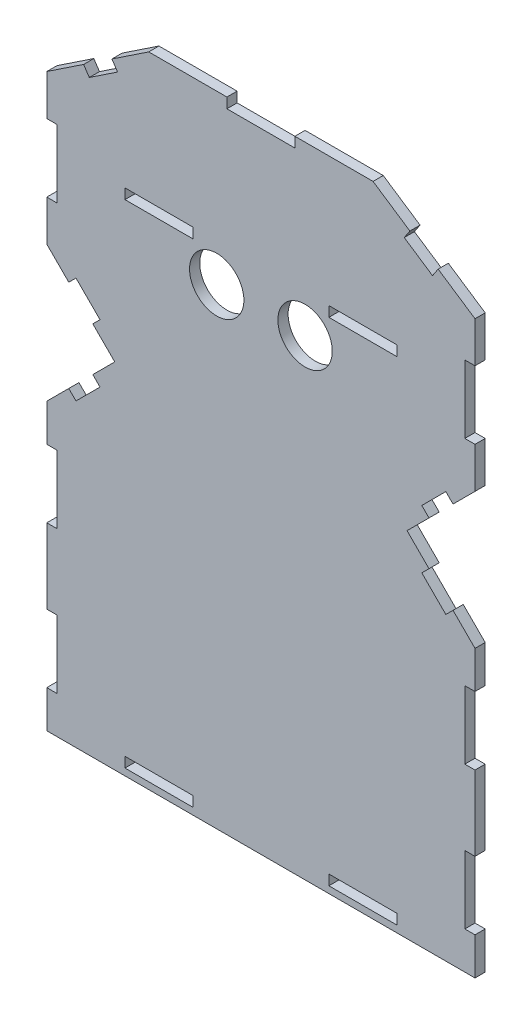
SolidWorks part; units mm, degrees
ref_plane "Front Plane" through (0, 0, 0) normal (0, 0, 1) x (1, 0, 0)
ref_plane "Top Plane" through (0, 0, 0) normal (0, 1, 0) x (1, 0, 0)
ref_plane "Right Plane" through (0, 0, 0) normal (1, 0, 0) x (0, 0, -1)
sketch "Sketch1" plane through (0, 0, 0) normal (0, 0, 1) x (1, 0, 0)
  line L0 (62.2747, 0) -> (62.2747, -11)
  line L1 (-33.7253, 104) -> (-10.7253, 104)
  line L2 (-63.7253, 84) -> (-63.7253, 72)
  line L3 (-63.7253, -84) -> (62.2747, -84)
  line L4 (62.2747, 84) -> (62.2747, 72)
  line L5 (-0.7253, -84) -> (-0.7253, -49.3815) construction
  line L6 (-63.7253, -84) -> (-63.7253, -80.5) construction
  line L7 (-63.7253, -80.5) -> (-60.7253, -80.5) construction
  line L8 (-63.7253, 84) -> (-52.8856, 91.2265)
  line L10 (-63.7253, 84) -> (-63.7253, 72) construction
  line L11 (-60.7253, -80.5) -> (-60.7253, -84) construction
  line L12 (-63.7253, 0) -> (-57.2608, 6.4645)
  line L13 (-43.7253, 20) -> (-50.1898, 26.4645)
  line L14 (62.2747, 0) -> (55.8102, 6.4645)
  line L15 (42.2747, 20) -> (48.7392, 26.4645)
  line L16 (-63.7253, 0) -> (-63.7253, -11)
  line L17 (62.2747, -80.5) -> (59.2747, -80.5) construction
  line L18 (-60.7253, -80.5) -> (59.2747, -80.5) construction
  line L19 (-0.7253, -80.5) -> (-60.7253, -80.5) construction
  line L20 (19.2747, -82) -> (19.2747, -79)
  line L21 (-40.7253, -82) -> (-20.7253, -82)
  line L22 (-40.7253, -82) -> (-40.7253, -79)
  line L23 (-40.7253, -79) -> (-20.7253, -79)
  line L24 (-20.7253, -82) -> (-20.7253, -79)
  line L25 (-40.7253, -82) -> (-20.7253, -79) construction
  line L26 (-40.7253, -79) -> (-20.7253, -82) construction
  line L27 (39.2747, -82) -> (19.2747, -82)
  line L28 (39.2747, -82) -> (39.2747, -79)
  line L29 (39.2747, -79) -> (19.2747, -79)
  line L30 (-63.7253, -84) -> (-62.221, -84) construction
  line L31 (-63.7253, -42) -> (-62.2253, -42) construction
  line L32 (-62.2253, -42) -> (-62.2253, 0) construction
  line L33 (-62.2253, 0) -> (-63.7253, 0) construction
  line L34 (-63.7253, -31) -> (-60.7253, -31)
  line L36 (-63.7253, -11) -> (-60.7253, -11)
  line L37 (-60.7253, -31) -> (-60.7253, -11)
  line L38 (-63.7253, -31) -> (-60.7253, -11) construction
  line L39 (-63.7253, -11) -> (-60.7253, -31) construction
  line L40 (-63.7253, -53) -> (-60.7253, -53)
  line L41 (-60.7253, -53) -> (-60.7253, -73)
  line L42 (-63.7253, -73) -> (-60.7253, -73)
  line L43 (-62.2253, -84) -> (-63.7253, -84) construction
  line L44 (62.2747, -53) -> (59.2747, -53)
  line L45 (59.2747, -53) -> (59.2747, -73)
  line L46 (62.2747, -73) -> (59.2747, -73)
  line L47 (62.2747, -31) -> (59.2747, -31)
  line L48 (62.2747, -11) -> (59.2747, -11)
  line L49 (59.2747, -31) -> (59.2747, -11)
  line L50 (-63.7253, -73) -> (-63.7253, -84)
  line L51 (62.2747, -73) -> (62.2747, -84)
  line L52 (62.2747, -31) -> (62.2747, -53)
  line L53 (-63.7253, -31) -> (-63.7253, -53)
  line L54 (-63.7253, 40) -> (-62.2253, 40) construction
  line L55 (-62.2253, 40) -> (-62.2253, 84) construction
  line L56 (-62.2253, 84) -> (-63.7253, 84) construction
  line L57 (-63.7253, 52) -> (-63.7253, 40)
  line L58 (-63.7253, 52) -> (-60.7253, 52)
  line L60 (-63.7253, 72) -> (-60.7253, 72)
  line L61 (-60.7253, 52) -> (-60.7253, 72)
  line L62 (-63.7253, 52) -> (-60.7253, 72) construction
  line L63 (-63.7253, 72) -> (-60.7253, 52) construction
  line L64 (-63.7253, 52) -> (-63.7253, 40) construction
  line L65 (62.2747, 52) -> (59.2747, 52)
  line L66 (59.2747, 52) -> (59.2747, 72)
  line L67 (62.2747, 72) -> (59.2747, 72)
  line L68 (62.2747, 52) -> (62.2747, 40)
  line L69 (-43.7253, 20) -> (-42.6646, 18.9393) construction
  line L70 (-63.7253, 0) -> (-62.6646, -1.0607) construction
  line L71 (-62.6646, -1.0607) -> (-42.6646, 18.9393) construction
  line L72 (-55.1395, 4.3431) -> (-57.2608, 6.4645)
  line L73 (-55.1395, 4.3431) -> (-48.0685, 11.4142)
  line L75 (-48.0685, 11.4142) -> (-50.1898, 13.5355)
  line L76 (-50.1898, 13.5355) -> (-43.7253, 20)
  line L77 (53.6889, 4.3431) -> (55.8102, 6.4645)
  line L78 (46.6178, 11.4142) -> (48.7392, 13.5355)
  line L79 (53.6889, 4.3431) -> (46.6178, 11.4142)
  line L80 (42.2747, 20) -> (5.8268, 20) construction
  line L81 (-55.1395, 35.6569) -> (-57.2608, 33.5355)
  line L82 (-48.0685, 28.5858) -> (-50.1898, 26.4645)
  line L83 (-55.1395, 35.6569) -> (-48.0685, 28.5858)
  line L84 (-57.2608, 33.5355) -> (-63.7253, 40)
  line L85 (46.6178, 28.5858) -> (48.7392, 26.4645)
  line L86 (53.6889, 35.6569) -> (55.8102, 33.5355)
  line L87 (53.6889, 35.6569) -> (46.6178, 28.5858)
  line L88 (55.8102, 33.5355) -> (62.2747, 40)
  line L89 (48.7392, 13.5355) -> (42.2747, 20)
  line L90 (-63.7253, 84) -> (-52.8856, 91.2265) construction
  line L92 (-52.8856, 91.2265) -> (-51.2215, 88.7303)
  line L93 (-44.5651, 96.7735) -> (-42.901, 94.2774)
  line L94 (-51.2215, 88.7303) -> (-42.901, 94.2774)
  line L95 (-44.5651, 96.7735) -> (-33.7253, 104)
  line L96 (-44.5651, 96.7735) -> (-33.7253, 104) construction
  line L97 (-33.7253, 104) -> (-63.7253, 84) construction
  line L98 (-48.7253, 94) -> (-47.0612, 91.5038) construction
  line L99 (51.4349, 91.2265) -> (49.7708, 88.7303)
  line L100 (49.7708, 88.7303) -> (41.4503, 94.2774)
  line L101 (43.1144, 96.7735) -> (41.4503, 94.2774)
  line L102 (32.2747, 104) -> (43.1144, 96.7735)
  line L103 (62.2747, 84) -> (51.4349, 91.2265)
  line L104 (-33.7253, 104) -> (-33.7253, 102.5) construction
  line L105 (-33.7253, 102.5) -> (32.2747, 102.5) construction
  line L106 (32.2747, 102.5) -> (32.2747, 104) construction
  line L107 (-10.7253, 101) -> (9.2747, 101)
  line L108 (-10.7253, 101) -> (-10.7253, 104)
  line L110 (9.2747, 101) -> (9.2747, 104)
  line L111 (-10.7253, 101) -> (9.2747, 104) construction
  line L112 (-10.7253, 104) -> (9.2747, 101) construction
  line L113 (9.2747, 104) -> (32.2747, 104)
  line L114 (-63.7253, 84) -> (62.2747, 84) construction
  line L115 (-0.7253, 84) -> (-0.7253, 64.3525) construction
  line L116 (-0.7253, 64.3525) -> (-60.7253, 64.3525) construction
  line L117 (39.2747, 62.8525) -> (39.2747, 65.8525)
  line L118 (-40.7253, 62.8525) -> (-20.7253, 62.8525)
  line L119 (-40.7253, 62.8525) -> (-40.7253, 65.8525)
  line L120 (-40.7253, 65.8525) -> (-20.7253, 65.8525)
  line L121 (-20.7253, 62.8525) -> (-20.7253, 65.8525)
  line L122 (-40.7253, 62.8525) -> (-20.7253, 65.8525) construction
  line L123 (-40.7253, 65.8525) -> (-20.7253, 62.8525) construction
  line L124 (39.2747, 62.8525) -> (19.2747, 62.8525)
  line L125 (19.2747, 62.8525) -> (19.2747, 65.8525)
  line L126 (39.2747, 65.8525) -> (19.2747, 65.8525)
  line L127 (-0.7253, 84) -> (-0.7253, 54.6888) construction
  line L128 (-0.7253, 54.6888) -> (-13.7253, 54.6888) construction
  circle A0 centre (-13.7253, 54.6888) radius 8
  circle A1 centre (12.2747, 54.6888) radius 8
  point P0 (0, 0)
  point P20 (-30.7253, -80.5)
  point P31 (-62.2253, -21)
  point P53 (-62.2253, 62)
  point P67 (-52.6646, 8.9393)
  point P94 (-0.7253, 102.5)
  point P103 (-30.7253, 64.3525)
  dimension "D39" = 16
  dimension "D1" = 84
  dimension "D2" = 126
  dimension "D3" = 20
  dimension "D4" = 30
  dimension "D5" = 20
  dimension "D6" = 20
  dimension "D7" = 44
  dimension "D8" = 20
  dimension "D9" = 30
  dimension "D10" = 20
  dimension "D11" = 20
  dimension "D12" = 84
  dimension "D13" = 44
  dimension "D14" = 20
  dimension "D15" = 3
  dimension "D16" = 3.5
  dimension "D17" = 20
  dimension "D18" = 3
  dimension "D19" = 1.5
  dimension "D20" = 20
  dimension "D21" = 3
  dimension "D22" = 1.5
  dimension "D23" = 1.5
  dimension "D24" = 20
  dimension "D25" = 3
  dimension "D26" = 10
  dimension "D27" = 1.5
  dimension "D28" = 48.0685
  dimension "D29" = 10
  dimension "D30" = 3
  dimension "D31" = 19.6475
  dimension "D32" = 20
  dimension "D33" = 3
  dimension "D34" = 60
  dimension "D35" = 20
  dimension "D36" = 3
  dimension "D37" = 29.3112
  dimension "D38" = 13
extrude "Boss-Extrude1" add sketch "Sketch1" along normal blind 3
